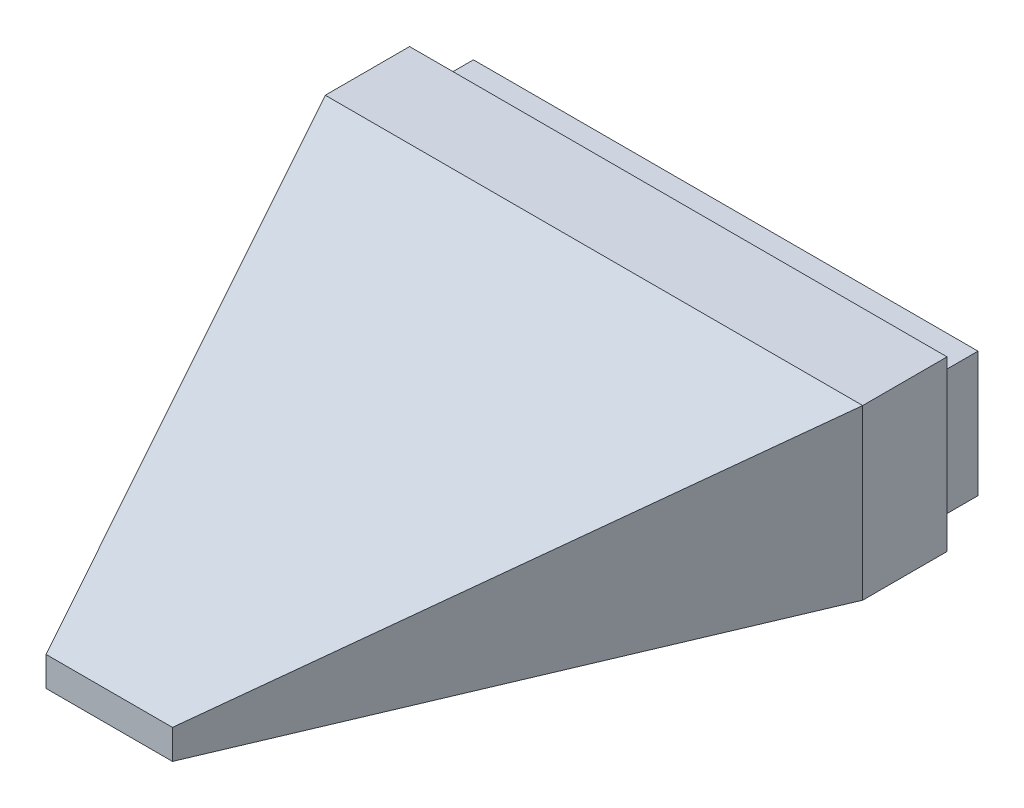
SolidWorks part; units mm, degrees
ref_plane "Alzado" through (0, 0, 0) normal (0, 0, 1) x (1, 0, 0)
ref_plane "Planta" through (0, 0, 0) normal (0, 1, 0) x (1, 0, 0)
ref_plane "Vista lateral" through (0, 0, 0) normal (1, 0, 0) x (0, 0, -1)
sketch "Croquis1" plane through (0, 0, 0) normal (0, 0, 1) x (1, 0, 0)
  line L1 (63.75, -20) -> (-63.75, -20)
  line L2 (63.75, -20) -> (63.75, 20)
  line L3 (63.75, 20) -> (-63.75, 20)
  line L4 (-63.75, -20) -> (-63.75, 20)
  line L5 (63.75, -20) -> (-63.75, 20) construction
  line L6 (63.75, 20) -> (-63.75, -20) construction
  point P0 (0, 0)
  dimension "D1" = 127.5
  dimension "D2" = 40
extrude "Saliente-Extruir2" add sketch "Croquis1" along normal blind 135
sketch "Croquis3" plane through (0, 0, 0) normal (0, 0, -1) x (-1, 0, 0)
  line L0 (-63.75, 20) -> (63.75, 20) construction
  line L1 (58.6, 14.85) -> (-61.1, 14.85)
  line L2 (58.6, 14.85) -> (58.6, -14.85)
  line L3 (58.6, -14.85) -> (-61.1, -14.85)
  line L4 (-61.1, 14.85) -> (-61.1, -14.85)
  line L5 (63.75, -20) -> (-63.75, -20) construction
  line L6 (63.75, 20) -> (63.75, -20) construction
  line L7 (-63.75, -20) -> (-63.75, 20) construction
  dimension "D1" = 5.15
  dimension "D2" = 5.15
  dimension "D3" = 5.15
  dimension "D4" = 2.65
extrude "Saliente-Extruir3" add sketch "Croquis3" along normal blind 10
sketch "Croquis4" plane through (-63.75, 0, 0) normal (-1, 0, 0) x (0, 0, 1)
  line L0 (20, 20) -> (135, -13)
  line L1 (135, 20) -> (0, 20) construction
  line L2 (135, 20) -> (135, -20) construction
  line L3 (135, -13) -> (135, -20)
  line L8 (20, 20) -> (79.5975, 49.3129)
  line L9 (79.5975, 49.3129) -> (161.8457, 28.2559)
  line L10 (161.8457, 28.2559) -> (135, -13)
  line M5 (135, -20) -> (135, 20)
  line M6 (135, 20) -> (0, 20)
  dimension "D1" = 7
extrude "Cortar-Extruir1" cut sketch "Croquis4" against normal blind 184 contours L0 M6 M5
sketch "Croquis5" plane through (0, 20, 0) normal (0, 1, 0) x (1, 0, 0)
  line L0 (-63.75, -20) -> (-15, -135)
  line L1 (-63.75, -135) -> (63.75, -135) construction
  line L2 (-15, -135) -> (15, -135)
  line L3 (15, -135) -> (63.75, -20)
  line L4 (63.75, -20) -> (107.1899, -122.4736)
  line L5 (107.1899, -122.4736) -> (58.694, -179.2521)
  line L6 (58.694, -179.2521) -> (-87.2839, -146.8497)
  line L7 (-87.2839, -146.8497) -> (-63.75, -20)
  point P5 (0, -135)
  point P12 (0, -135)
  dimension "D1" = 30
extrude "Cortar-Extruir2" cut sketch "Croquis5" against normal blind 184
shell "Vaciado1" thickness 5
